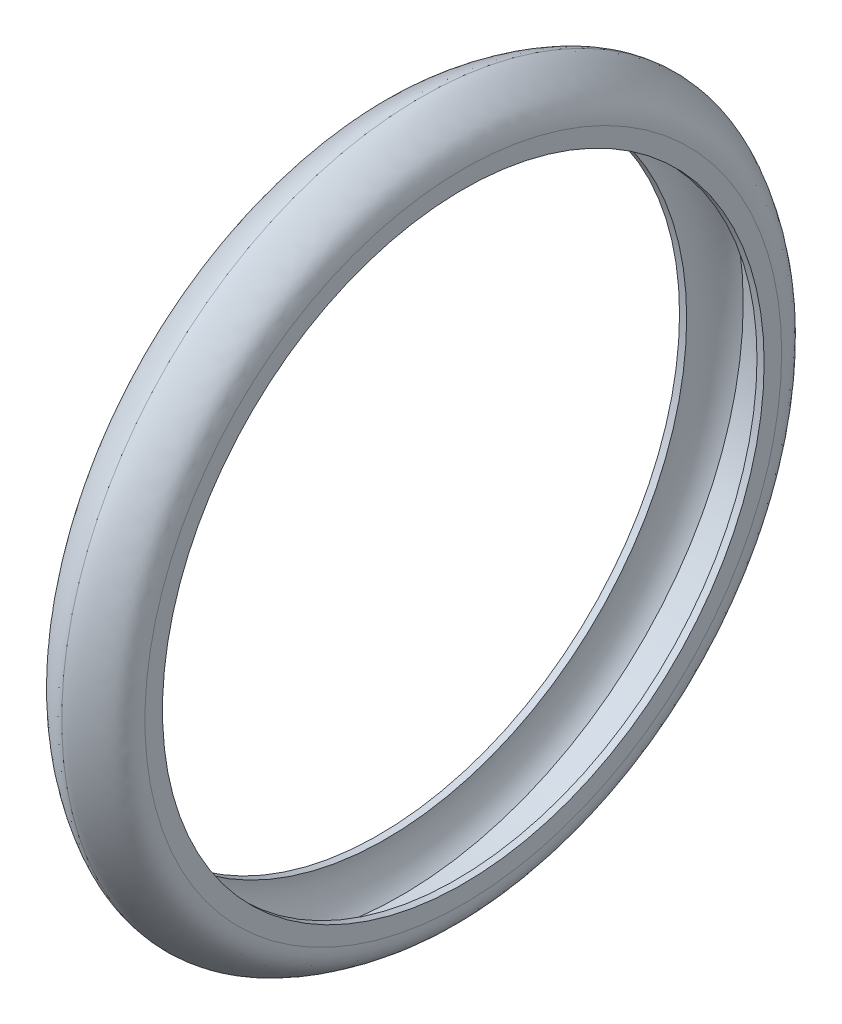
SolidWorks part; units mm, degrees
material "Silicon Rubber"
ref_plane "Front Plane" through (0, 0, 0) normal (0, 0, 1) x (1, 0, 0)
ref_plane "Top Plane" through (0, 0, 0) normal (0, 1, 0) x (1, 0, 0)
ref_plane "Right Plane" through (0, 0, 0) normal (1, 0, 0) x (0, 0, -1)
sketch "Sketch1" plane through (0, 0, 0) normal (0, 0, 1) x (1, 0, 0)
  line L0 (15.5774, 0) -> (-14.2304, 0) construction
  line L1 (0, 0) -> (0, 32.512)
  line L5 (-1.905, 32.512) -> (1.905, 32.512) construction
  line L6 (1.905, 32.512) -> (-1.905, 32.512)
  line L7 (4.018, 30.2387) -> (4.018, 28.575)
  line L8 (4.018, 28.575) -> (3.3392, 28.575)
  line L11 (-1.905, 32.512) -> (-1.905, 29.845) construction
  line L12 (-1.905, 29.845) -> (-3.3392, 29.845) construction
  line L13 (-3.3392, 29.845) -> (-3.3392, 28.575) construction
  line L14 (0, 32.512) -> (0, 36.2122) construction
  line L15 (-4.018, 30.2387) -> (-4.018, 28.575)
  line L16 (-4.018, 28.575) -> (-3.3392, 28.575)
  arc A2 (-1.905, 32.512) -> (-3.3392, 28.575) centre (1.1436, 29.1717) ccw
  arc A3 (1.905, 32.512) -> (3.3392, 28.575) centre (-1.1436, 29.1717) cw
  spline S0 degree 3 poles (0, 34.1284) (-0.661, 34.1186) (-3.4693, 32.4507) (-4.018, 31.5432) (-4.018, 30.2387) knots 0.504084 0.504084 0.504084 0.504084 0.667615 1 1 1 1
  spline S1 degree 3 poles (0, 34.1284) (0.661, 34.1186) (3.4693, 32.4507) (4.018, 31.5432) (4.018, 30.2387) knots 0.504084 0.504084 0.504084 0.504084 0.667615 1 1 1 1
  point P8 (0, 32.512)
  dimension "D2" = 2.667
  dimension "D4" = 6.063
  dimension "D7" = 4.5223
  dimension "D9" = 4.5223
  dimension "D5" = 6.063
  dimension "D1" = 32.512
  dimension "D3" = 1.27
  dimension "D6" = 1.6637
  dimension "D8" = 3.81
  dimension "D10" = 0.6789
  dimension "D11" = 5.5534
  dimension "D12" = 3.8897
  dimension "D13" = 1.6637
  dimension "D14" = 1.6164
revolve "Revolve2" add sketch "Sketch1" angle 360 about L0
